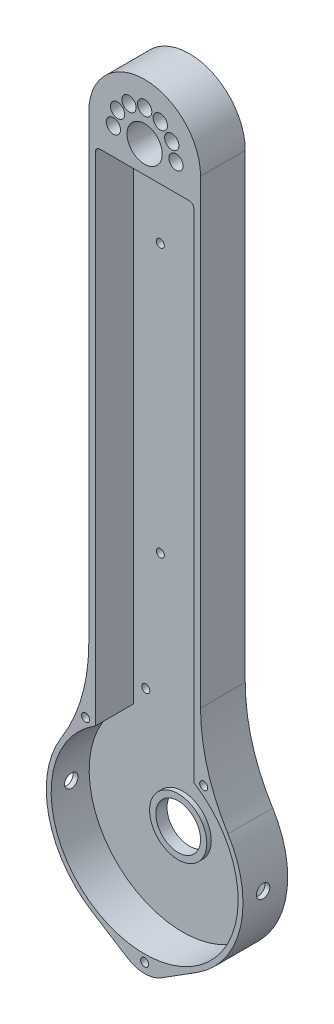
SolidWorks part; units mm, degrees
ref_plane "Front Plane" through (0, 0, 0) normal (0, 0, 1) x (1, 0, 0)
ref_plane "Top Plane" through (0, 0, 0) normal (0, 1, 0) x (1, 0, 0)
ref_plane "Right Plane" through (0, 0, 0) normal (1, 0, 0) x (0, 0, -1)
sketch "Sketch1" plane through (0, 0, 0) normal (0, 0, 1) x (1, 0, 0)
  line L0 (0, 0) -> (0, 246.3118) construction
  line L1 (-15.875, 246.3118) -> (-15.875, 115.4777)
  line L2 (15.875, 246.3118) -> (15.875, 115.4777)
  line L3 (-26.8601, 40.5718) -> (38.5035, 40.5718) construction
  line L4 (-4.7378, 43.5558) -> (-14.8909, 49.9506)
  line L5 (4.7378, 43.5558) -> (14.8903, 49.9502)
  arc A0 (15.875, 246.3118) -> (-15.875, 246.3118) centre (0, 246.3118) ccw
  arc A1 (-23.6589, 88.4545) -> (-14.8909, 49.9506) centre (0, 73.5918) ccw
  arc A2 (-15.875, 115.4777) -> (-23.6589, 88.4545) centre (-66.675, 115.4777) cw
  arc A3 (15.875, 115.4777) -> (23.6589, 88.4545) centre (66.675, 115.4777) ccw
  arc A4 (4.7378, 43.5558) -> (-4.7378, 43.5558) centre (0, 51.0781) cw
  arc A5 (14.8903, 49.9502) -> (23.6589, 88.4545) centre (0, 73.5918) ccw
  point P19 (0, 40.5718)
  dimension "D1" = 172.72
  dimension "D2" = 31.75
  dimension "D3" = 55.88
  dimension "D4" = 50.8
  dimension "D5" = 50.8
  dimension "D7" = 8.89
  dimension "D6" = 33.02
extrude "Boss-Extrude1" add sketch "Sketch1" along normal blind 12.7 contours L1 A2 A1 L4 A4 L5 A5 A3 L2 A0
sketch "Sketch2" plane through (0, 0, 12.7) normal (0, 0, 1) x (1, 0, 0)
  circle A0 centre (0, 246.3118) radius 5
extrude "Cut-Extrude1" cut sketch "Sketch2" against normal blind 33
sketch "Sketch3" plane through (0, 0, 12.7) normal (0, 0, 1) x (1, 0, 0)
  line L0 (0, 246.3118) -> (-28.894, 246.3118) construction
  line L1 (0, 246.3118) -> (17.78, 246.3118) construction
  line L2 (0, 246.3118) -> (0, 272.8746) construction
  circle A0 centre (0, 246.3118) radius 8.89 construction
  circle A1 centre (-8.89, 246.3118) radius 2.032
  circle A2 centre (-7.6974, 250.7548) radius 2.032
  circle A3 centre (-4.4436, 254.0068) radius 2.032
  circle A4 centre (0, 255.197) radius 2.032
  circle A5 centre (4.4436, 254.0068) radius 2.032
  circle A6 centre (7.6974, 250.7548) radius 2.032
  circle A7 centre (8.89, 246.3118) radius 2.032
  point P22 (0, 246.307)
  dimension "D1" = 7
extrude "Cut-Extrude2" cut sketch "Sketch3" against normal blind 7.62
sketch "Sketch4" plane through (0, 0, 12.7) normal (0, 0, 1) x (1, 0, 0)
  line L0 (0, 246.3118) -> (0, -1.3188) construction
  line L1 (-12.7, 238.6918) -> (12.7, 238.6918)
  line L2 (-13.97, 237.4218) -> (-13.97, 96.1754)
  line L3 (13.97, 237.4218) -> (13.97, 96.1754)
  arc A0 (-13.97, 96.1754) -> (13.97, 96.1754) centre (0, 73.5918) ccw
  arc A1 (13.97, 237.4218) -> (12.7, 238.6918) centre (12.7, 237.4218) ccw
  arc A2 (-12.7, 238.6918) -> (-13.97, 237.4218) centre (-12.7, 237.4218) ccw
  point P10 (13.97, 238.6918)
  point P14 (-13.97, 238.6918)
  dimension "D1" = 27.94
  dimension "D4" = 1.27
  dimension "D2" = 13.97
  dimension "D3" = 165.1
extrude "Cut-Extrude3" cut sketch "Sketch4" against normal blind 10.795
sketch "Sketch5" plane through (0, 0, 1.905) normal (0, 0, 1) x (1, 0, 0)
  line L0 (0, 246.3118) -> (0, 210.5841) construction
  circle A0 centre (0, 235.3118) radius 1.5875
  circle A2 centre (0, 246.3118) radius 5 construction
  dimension "D1" = 11
extrude "Cut-Extrude4" cut sketch "Sketch5" against normal blind 10
sketch "Sketch6" plane through (0, 0, 0) normal (0, 0, -1) x (-1, 0, 0)
  line L0 (0, 235.3118) -> (0, 244.6749) construction
  line L1 (-1.5875, 246.4808) -> (1.5875, 246.4808)
  line L2 (-1.5875, 246.4808) -> (-1.5875, 235.3118)
  line L3 (-1.5875, 235.3118) -> (1.5875, 235.3118)
  line L4 (1.5875, 246.4808) -> (1.5875, 235.3118)
  circle A0 centre (0, 235.3118) radius 1.5875 construction
  dimension "D1" = 3.175
  dimension "D2" = 0
  dimension "D3" = 1.5875
extrude "Cut-Extrude5" cut sketch "Sketch6" against normal blind 0.635
sketch "Sketch7" plane through (0, 0, 0) normal (0, 0, -1) x (-1, 0, 0)
  circle A0 centre (0, 246.3118) radius 6
extrude "Cut-Extrude6" cut sketch "Sketch7" against normal blind 1.5494 contours A0
sketch "Sketch9" plane through (0, 0, 1.905) normal (0, 0, 1) x (1, 0, 0)
  circle A0 centre (0, 73.5918) radius 8.128
extrude "Boss-Extrude2" add sketch "Sketch9" along normal blind 1.27
sketch "Sketch10" plane through (0, 0, 3.175) normal (0, 0, 1) x (1, 0, 0)
  circle A0 centre (0, 73.5918) radius 6.35
extrude "Cut-Extrude7" cut sketch "Sketch10" against normal blind 22.27
sketch "Sketch11" plane through (0, 0, 1.905) normal (0, 0, 1) x (1, 0, 0)
  line L0 (0, 73.5918) -> (0, 125.7903) construction
  circle A0 centre (-10.4775, 101.7096) radius 1.143
  circle A1 centre (10.4775, 101.7096) radius 1.143
  dimension "D1" = 20.955
  dimension "D2" = 10.4775
  dimension "D3" = 28.1178
extrude "Cut-Extrude8" cut sketch "Sketch11" against normal blind 49.276
sketch "Sketch12" plane through (0, 0, 12.7) normal (0, 0, 1) x (1, 0, 0)
  line L0 (0, 73.5918) -> (0, 31.8885) construction
  circle A0 centre (-16.764, 96.8328) radius 1.143
  circle A1 centre (16.764, 96.8328) radius 1.143
  circle A2 centre (0, 45.0168) radius 1.143
  circle A3 centre (0, 73.5918) radius 6.35 construction
  circle A4 centre (0, 73.5918) radius 6.35 construction
  dimension "D1" = 28.575
  dimension "D2" = 16.764
  dimension "D3" = 16.764
  dimension "D4" = 23.241
  dimension "D5" = 23.241
extrude "Cut-Extrude9" cut sketch "Sketch12" against normal blind 49.276
sketch "Sketch13" plane through (0, 0, 1.905) normal (0, 0, 1) x (1, 0, 0)
  line L0 (-6.35, 213.2918) -> (6.35, 213.2918) construction
  line L1 (0, 235.3118) -> (0, 201.4768) construction
  line L2 (12.7, 238.6918) -> (-12.7, 238.6918) construction
  circle A0 centre (-6.35, 213.2918) radius 1.143
  circle A1 centre (6.35, 213.2918) radius 1.143
  circle A2 centre (-6.35, 137.0918) radius 1.143
  circle A3 centre (6.35, 137.0918) radius 1.143
  dimension "D1" = 6.35
  dimension "D3" = 76.2
  dimension "D2" = 25.4
  dimension "D4" = 76.2
  dimension "D5" = 12.7
  dimension "D6" = 6.35
extrude "Cut-Extrude10" cut sketch "Sketch13" against normal blind 49.276
sketch3d "3DSketch2" plane through (0, 0, 0) normal (0, 0, 1) x (1, 0, 0)
  dimension "D1" = 15.875
sketch "Sketch15" plane through (0, 0, 0) normal (-1, 0, 0) x (0, 0, 1)
  line L0 (0, 0) -> (0, 129.1934) construction
  line L2 (12.1508, 73.5918) -> (-8.366, 73.5918) construction
  line L3 (12.7, 73.5918) -> (0, 73.5918) construction
  line L4 (6.985, 81.6202) -> (6.985, 64.2387) construction
  circle A0 centre (6.985, 73.5918) radius 1.905
  dimension "D1" = 0
  dimension "D2" = 6.985
extrude "Cut-Extrude11" cut sketch "Sketch15" against normal blind 50.8 and the other way blind 50.8
